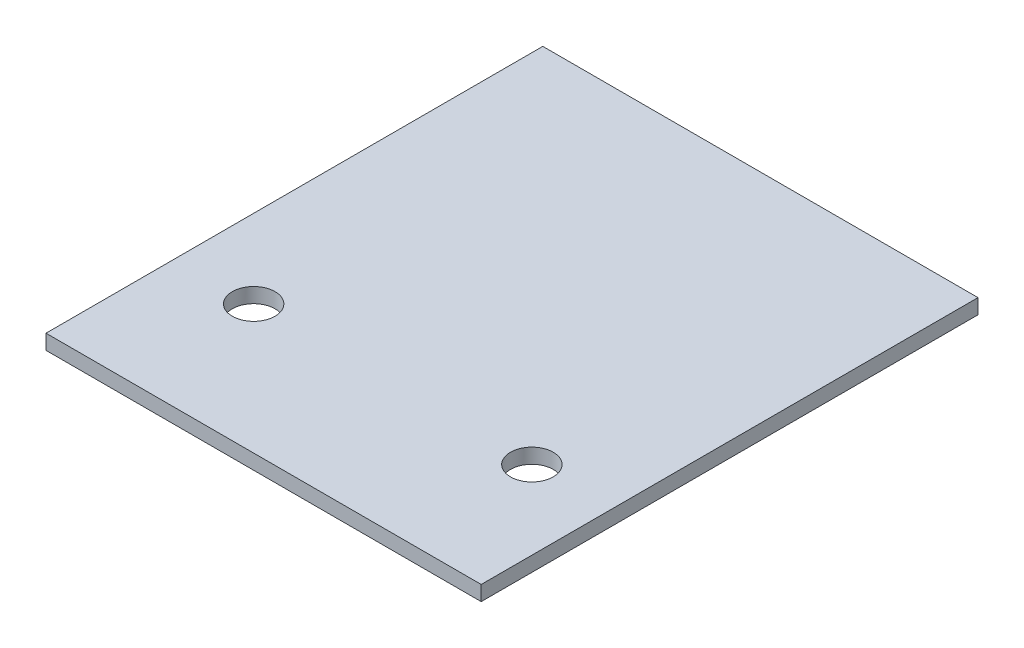
SolidWorks part; units mm, degrees
ref_plane "前视基准面" through (0, 0, 0) normal (0, 0, 1) x (1, 0, 0)
ref_plane "上视基准面" through (0, 0, 0) normal (0, 1, 0) x (1, 0, 0)
ref_plane "右视基准面" through (0, 0, 0) normal (1, 0, 0) x (0, 0, -1)
sketch "草图1" plane through (0, 0, 0) normal (0, 1, 0) x (1, 0, 0)
  line L1 (-21.9, -25) -> (21.9, -25)
  line L2 (-21.9, -25) -> (-21.9, 25)
  line L3 (-21.9, 25) -> (21.9, 25)
  line L4 (21.9, -25) -> (21.9, 25)
  line L5 (-21.9, -25) -> (21.9, 25) construction
  line L6 (-21.9, 25) -> (21.9, -25) construction
  point P0 (0, 0)
  dimension "D1" = 50
  dimension "D2" = 43.8
extrude "凸台-拉伸1" add sketch "草图1" along normal blind 1.5
hole_wizard "M4 间隙孔1" positions "草图3" profile "草图2" hole size "M4" standard "GB"
sketch "草图3" plane through (0, 1.5, 0) normal (0, 1, 0) x (1, 0, 0)
  line L0 (0, 0) -> (0, 38.0215) construction
  line L2 (-21.9, -25) -> (21.9, -25) construction
  point P0 (-14, -12)
  point P2 (14, -12)
  dimension "D1" = 28
  dimension "D2" = 13
sketch "草图2" plane through (-14, 1.5, 12) normal (1, 0, 0) x (0, 0, 1)
  line L0 (0, 0) -> (0, 3.2919)
  line L1 (0, 3.2919) -> (2.15, 2)
  line L2 (2.15, 2) -> (2.15, 0)
  line L5 (2.15, 0) -> (0, 0)
  line L10 (0, 3.2919) -> (-2.15, 2) construction
  line L11 (0, -6.35) -> (0, 107.95) construction
  dimension "孔直径" = 4.3
  dimension "孔深度" = 2
  dimension "导头角度" = 118
